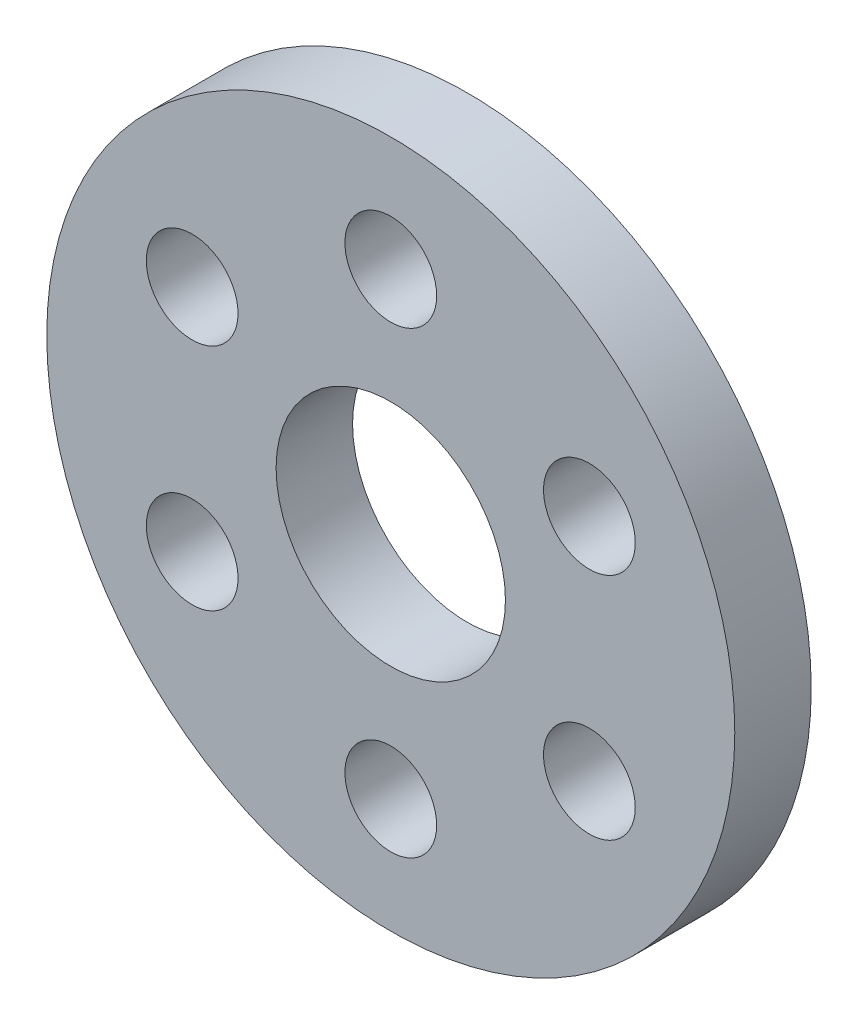
SolidWorks part; units mm, degrees
material "S-Glass Fiber"
ref_plane "Front Plane" through (0, 0, 0) normal (0, 0, 1) x (1, 0, 0)
ref_plane "Top Plane" through (0, 0, 0) normal (0, 1, 0) x (1, 0, 0)
ref_plane "Right Plane" through (0, 0, 0) normal (1, 0, 0) x (0, 0, -1)
sketch "Sketch1" plane through (0, 0, 0) normal (0, 0, 1) x (1, 0, 0)
  line L0 (0, 0) -> (-29728.8003, 0) construction
  line L1 (0, 0) -> (0, 29728.8003) construction
  circle A0 centre (0, 0) radius 22.5
  circle A1 centre (0, 0) radius 67.5
  circle A2 centre (0, -45) radius 9
  circle A3 centre (38.9711, -22.5) radius 9
  circle A4 centre (38.9711, 22.5) radius 9
  circle A5 centre (0, 45) radius 9
  circle A6 centre (-38.9711, 22.5) radius 9
  circle A7 centre (-38.9711, -22.5) radius 9
  point P23 (0, 0)
  dimension "D1" = 45
  dimension "D2" = 135
  dimension "D3" = 18
  dimension "D4" = 45
extrude "Boss-Extrude1" add sketch "Sketch1" along normal blind 15
